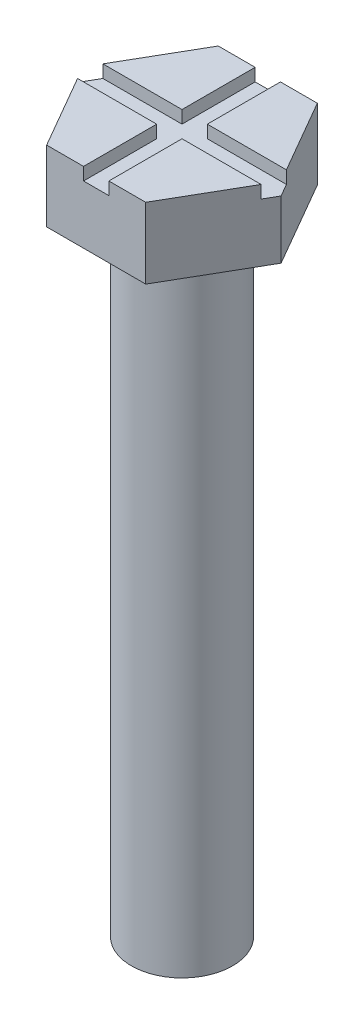
SolidWorks part; units mm, degrees
material "Alloy Steel"
ref_plane "Front" through (0, 0, 0) normal (0, 0, 1) x (1, 0, 0)
ref_plane "Top" through (0, 0, 0) normal (0, 1, 0) x (1, 0, 0)
ref_plane "Right" through (0, 0, 0) normal (1, 0, 0) x (0, 0, -1)
sketch "Sketch1" plane through (0, 0, 0) normal (0, 1, 0) x (1, 0, 0)
  line L1 (1.9572, -3.39) -> (3.9144, 0)
  line L2 (3.9144, 0) -> (1.9572, 3.39)
  line L3 (1.9572, 3.39) -> (-1.9572, 3.39)
  line L4 (-1.9572, 3.39) -> (-3.9144, 0)
  line L5 (-3.9144, 0) -> (-1.9572, -3.39)
  line L6 (-1.9572, -3.39) -> (1.9572, -3.39)
  circle A0 centre (0, 0) radius 3.39 construction
  dimension "D1" = 6.78
extrude "Boss-Extrude1" add sketch "Sketch1" along normal blind 2.8
sketch "Sketch2" plane through (0, 2.8, 0) normal (0, 1, 0) x (1, 0, 0)
  line L0 (-1.9572, -3.39) -> (1.9572, -3.39) construction
  line L1 (-0.5, 3.39) -> (0.5, 3.39)
  line L2 (-0.5, 3.39) -> (-0.5, 0.5)
  line L3 (-0.5, -3.39) -> (0.5, -3.39)
  line L4 (0.5, 3.39) -> (0.5, 0.5)
  line L5 (1.9572, 3.39) -> (-1.9572, 3.39) construction
  line L6 (-3.9144, 0.5) -> (-0.5, 0.5)
  line L9 (-3.9144, 0.5) -> (-3.9144, -0.5)
  line L10 (-3.9144, -0.5) -> (-0.5, -0.5)
  line L11 (3.9144, 0.5) -> (3.9144, -0.5)
  line L16 (0.5, 0.5) -> (3.9144, 0.5)
  line L18 (-0.5, -0.5) -> (-0.5, -3.39)
  line L20 (0.5, -0.5) -> (0.5, -3.39)
  line L21 (0.5, -0.5) -> (3.9144, -0.5)
  point P0 (0, 0)
  point P8 (0, 0)
  point P15 (-0.6852, 0.2195)
  point P16 (0.5, 0.4556)
  point P17 (0.5, 0.5)
  point P22 (3.9144, 0)
  point P25 (-0.5, 0.5)
  point P26 (3.9144, -0.5)
  dimension "D1" = 1
  dimension "D2" = 1
extrude "Cut-Extrude1" cut sketch "Sketch2" against normal blind 0.5
sketch "Sketch3" plane through (0, 0, 0) normal (0, -1, 0) x (1, 0, 0)
  circle A0 centre (0, 0) radius 2
  dimension "D1" = 4
extrude "Boss-Extrude2" add sketch "Sketch3" along normal blind 25
